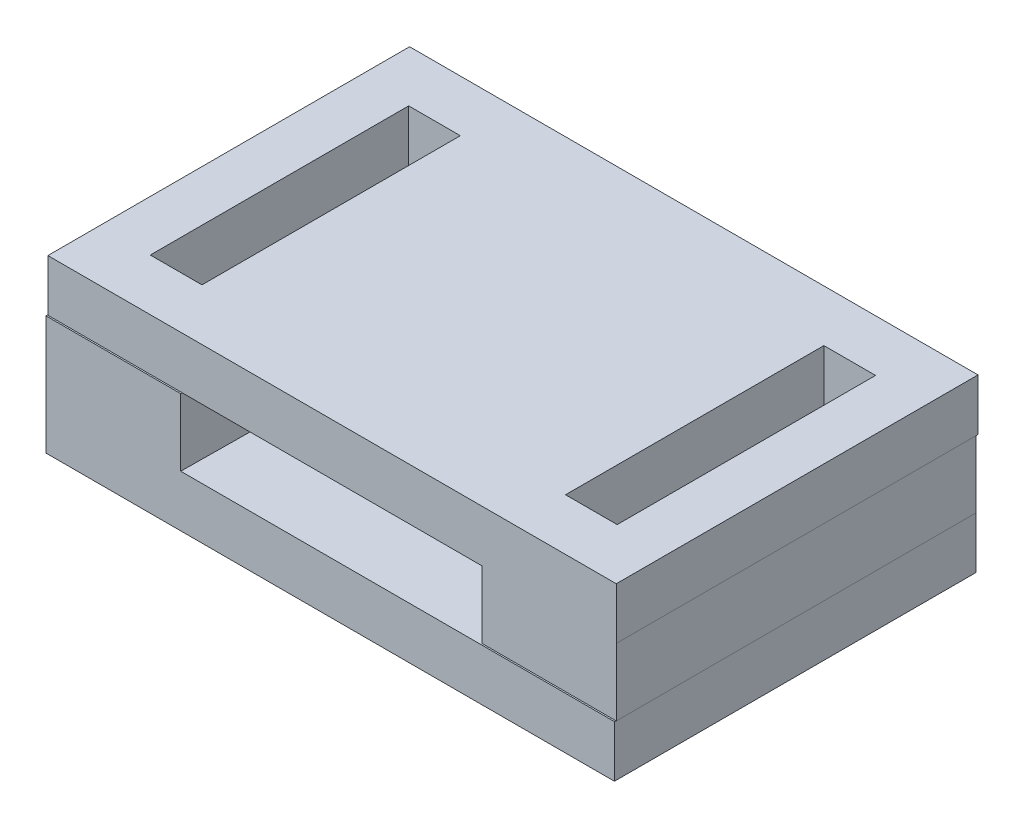
SolidWorks part; units mm, degrees
ref_plane "Front Plane" through (0, 0, 0) normal (0, 0, 1) x (1, 0, 0)
ref_plane "Top Plane" through (0, 0, 0) normal (0, 1, 0) x (1, 0, 0)
ref_plane "Right Plane" through (0, 0, 0) normal (1, 0, 0) x (0, 0, -1)
sketch "Sketch1" plane through (0, 0, 0) normal (0, 1, 0) x (1, 0, 0)
  line L0 (-13.97, 0) -> (-10.2049, 0) construction
  line L1 (-13.97, -8.89) -> (13.97, -8.89)
  line L2 (-13.97, -8.89) -> (-13.97, 8.89)
  line L3 (-13.97, 8.89) -> (13.97, 8.89)
  line L4 (13.97, -8.89) -> (13.97, 8.89)
  line L5 (-13.97, -8.89) -> (13.97, 8.89) construction
  line L6 (-13.97, 8.89) -> (13.97, -8.89) construction
  line L7 (0, -1000) -> (0, 49000) construction
  line L8 (-8.9349, -6.35) -> (-11.4749, -6.35)
  line L9 (-8.9349, -6.35) -> (-8.9349, 6.35)
  line L10 (-8.9349, 6.35) -> (-11.4749, 6.35)
  line L11 (-11.4749, -6.35) -> (-11.4749, 6.35)
  line L12 (-8.9349, -6.35) -> (-11.4749, 6.35) construction
  line L13 (-8.9349, 6.35) -> (-11.4749, -6.35) construction
  line L14 (8.9349, 6.35) -> (11.4749, 6.35)
  line L15 (11.4749, -6.35) -> (11.4749, 6.35)
  line L16 (8.9349, -6.35) -> (11.4749, -6.35)
  line L17 (8.9349, -6.35) -> (8.9349, 6.35)
  point P0 (0, 0)
  dimension "D1" = 17.78
  dimension "D2" = 27.94
  dimension "D3" = 12.7
  dimension "D4" = 2.54
extrude "Boss-Extrude2" add sketch "Sketch1" along normal blind 2.54
sketch "Sketch3" plane through (0, 2.54, 0) normal (0, 1, 0) x (1, 0, 0)
  line L0 (0, 8.89) -> (0, 2.54) construction
  line L1 (13.97, 8.89) -> (-13.97, 8.89) construction
  line L2 (5.3189, 2.54) -> (-5.3189, 2.54) construction
  circle A0 centre (-5.3189, 2.54) radius 1.27
  circle A1 centre (5.3189, 2.54) radius 1.27
extrude "Boss-Extrude3" add sketch "Sketch3" along normal blind 3.302
sketch3d "3DSketch2" plane through (0, 0, 0) normal (0, 0, 1) x (1, 0, 0)
  dimension "D1" = 3.302
sketch "Sketch4" plane through (0, 5.842, 0) normal (0, 1, 0) x (1, 0, 0)
  line L0 (-13.9518, 0.0729) -> (-10.1867, 0.0729) construction
  line L1 (-13.9518, -8.8171) -> (13.9882, -8.8171)
  line L2 (-13.9518, -8.8171) -> (-13.9518, 8.9629)
  line L3 (-13.9518, 8.9629) -> (13.9882, 8.9629)
  line L4 (13.9882, -8.8171) -> (13.9882, 8.9629)
  line L5 (-13.9518, -8.8171) -> (13.9882, 8.9629) construction
  line L6 (-13.9518, 8.9629) -> (13.9882, -8.8171) construction
  line L7 (0.0182, -999.9271) -> (0.0182, 49000.0729) construction
  line L8 (-8.9167, -6.2771) -> (-11.4567, -6.2771)
  line L9 (-8.9167, -6.2771) -> (-8.9167, 6.4229)
  line L10 (-8.9167, 6.4229) -> (-11.4567, 6.4229)
  line L11 (-11.4567, -6.2771) -> (-11.4567, 6.4229)
  line L12 (-8.9167, -6.2771) -> (-11.4567, 6.4229) construction
  line L13 (-8.9167, 6.4229) -> (-11.4567, -6.2771) construction
  line L14 (8.9531, 6.4229) -> (11.4931, 6.4229)
  line L15 (11.4931, -6.2771) -> (11.4931, 6.4229)
  line L16 (8.9531, -6.2771) -> (11.4931, -6.2771)
  line L17 (8.9531, -6.2771) -> (8.9531, 6.4229)
  point P0 (0.0182, 0.0729)
  dimension "D1" = 17.78
  dimension "D2" = 27.94
  dimension "D3" = 12.7
  dimension "D4" = 2.54
sketch "Sketch6" plane through (0, 2.54, 0) normal (0, 1, 0) x (1, 0, 0)
  line L0 (0.0182, 8.9629) -> (0.0182, -1.9707) construction
  line L1 (-13.9518, 8.9629) -> (13.9882, 8.9629) construction
  line L2 (0.0182, -200999.9271) -> (0.0182, 249000.0729) construction
  line L3 (-13.9518, -8.8171) -> (13.9882, 8.9629) construction
  line L8 (-7.2156, 4.7603) -> (7.3842, 4.7603)
  line L9 (11.4749, 6.35) -> (8.9713, 6.35)
  line L10 (-13.97, -8.89) -> (-13.97, 8.89)
  line L11 (-13.97, 8.89) -> (13.97, 8.89)
  line L12 (13.97, 8.89) -> (13.9882, -8.8171)
  line L13 (13.9882, -8.8171) -> (7.3842, -8.8171)
  line L14 (-13.9518, -8.8171) -> (13.9882, -8.8171) construction
  line L15 (7.3842, -8.8171) -> (7.3842, 4.7603)
  line L16 (-7.2156, 4.7603) -> (-7.3478, -8.89)
  line L17 (-13.97, -8.89) -> (13.97, -8.89) construction
  line L18 (-7.3478, -8.89) -> (-13.97, -8.89)
  line L19 (-11.4385, -6.2042) -> (-8.9349, -6.2042)
  line L20 (-11.4385, -6.2042) -> (-11.4385, 6.35)
  line L21 (-11.4385, 6.35) -> (-8.9349, 6.35)
  line L22 (-8.9349, -6.2042) -> (-8.9349, 6.35)
  line L23 (-11.4385, -6.2042) -> (-8.9349, 6.35) construction
  line L24 (-11.4385, 6.35) -> (-8.9349, -6.2042) construction
  line L25 (8.9713, -6.2042) -> (8.9713, 6.35)
  line L26 (11.4749, -6.2042) -> (8.9713, -6.2042)
  line L27 (11.4749, -6.2042) -> (11.4749, 6.35)
  line L28 (11.4749, 6.35) -> (8.9713, -6.2042) construction
  line L29 (11.4749, -6.2042) -> (8.9713, 6.35) construction
  point P7 (-10.1867, 0.0729)
  point P35 (10.2231, 0.0729)
extrude "Boss-Extrude6" add sketch "Sketch6" along normal blind 3.302
extrude "Boss-Extrude7" add sketch "Sketch4" along normal blind 2.54
